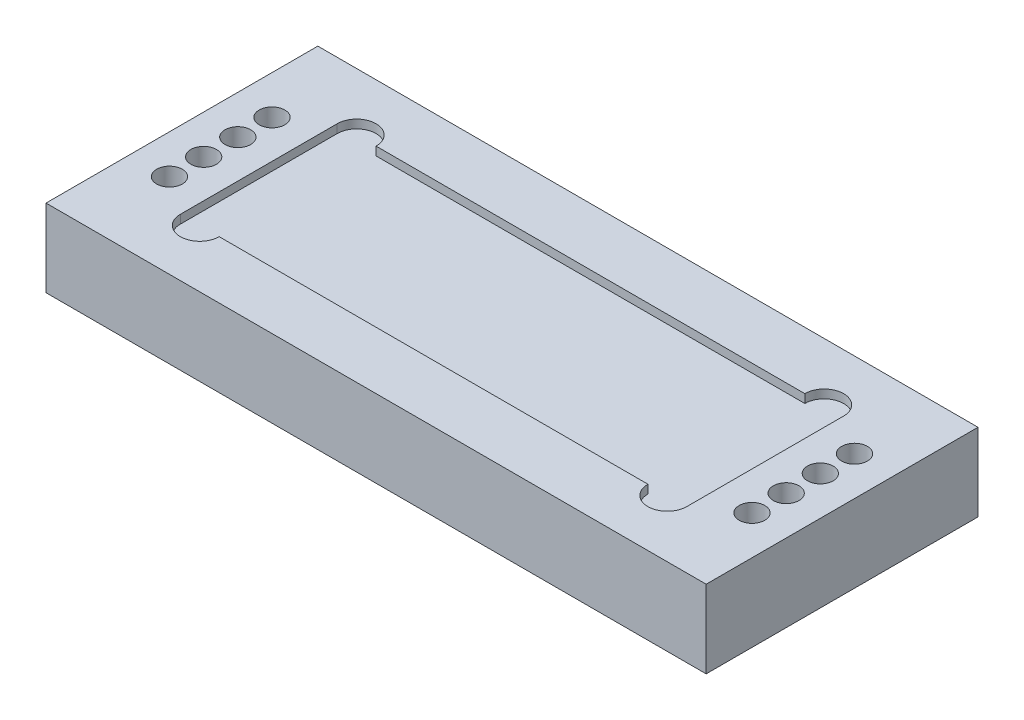
SolidWorks part; units mm, degrees
ref_plane "Front Plane" through (0, 0, 0) normal (0, 0, 1) x (1, 0, 0)
ref_plane "Top Plane" through (0, 0, 0) normal (0, 1, 0) x (1, 0, 0)
ref_plane "Right Plane" through (0, 0, 0) normal (1, 0, 0) x (0, 0, -1)
sketch "Sketch1" plane through (0, 0, 0) normal (0, 1, 0) x (1, 0, 0)
  line L1 (-53.975, 22.225) -> (53.975, 22.225)
  line L2 (-53.975, 22.225) -> (-53.975, -22.225)
  line L3 (-53.975, -22.225) -> (53.975, -22.225)
  line L4 (53.975, 22.225) -> (53.975, -22.225)
  line L5 (-35.052, 12.827) -> (35.052, 12.827) construction
  line L6 (-41.402, 12.827) -> (-41.402, -12.827) construction
  line L7 (-35.052, -12.827) -> (35.052, -12.827) construction
  line L8 (41.402, 12.827) -> (41.402, -12.827) construction
  arc A4 (-35.052, 12.827) -> (-41.402, 12.827) centre (-38.227, 12.827) ccw construction
  arc A5 (-41.402, -12.827) -> (-35.052, -12.827) centre (-38.227, -12.827) ccw construction
  arc A6 (41.402, 12.827) -> (35.052, 12.827) centre (38.227, 12.827) ccw construction
  arc A7 (35.052, -12.827) -> (41.402, -12.827) centre (38.227, -12.827) ccw construction
  point P8 (0, 12.827)
  point P22 (41.402, 0)
  point P24 (0, 22.225)
  point P27 (-53.975, 0)
  dimension "D1" = 3.175
  dimension "D2" = 82.804
  dimension "D3" = 25.654
  dimension "D4" = 107.95
  dimension "D5" = 44.45
extrude "Boss-Extrude1" add sketch "Sketch1" against normal blind 12.7
sketch "Sketch2" plane through (0, 0, 0) normal (0, 1, 0) x (1, 0, 0)
  line L4 (41.402, 12.827) -> (41.402, -12.827) construction
  line L5 (-35.052, -12.827) -> (35.052, -12.827) construction
  line L6 (-41.402, 12.827) -> (-41.402, -12.827) construction
  line L7 (-35.052, 12.827) -> (35.052, 12.827) construction
  line L8 (41.402, 12.827) -> (41.402, -12.827)
  line L9 (-35.052, -12.827) -> (35.052, -12.827)
  line L10 (-41.402, 12.827) -> (-41.402, -12.827)
  line L11 (-35.052, 12.827) -> (35.052, 12.827)
  arc A4 (35.052, -12.827) -> (41.402, -12.827) centre (38.227, -12.827) ccw construction
  arc A5 (-41.402, -12.827) -> (-35.052, -12.827) centre (-38.227, -12.827) ccw construction
  arc A6 (-35.052, 12.827) -> (-41.402, 12.827) centre (-38.227, 12.827) ccw construction
  arc A7 (41.402, 12.827) -> (35.052, 12.827) centre (38.227, 12.827) ccw construction
  arc A8 (35.052, -12.827) -> (41.402, -12.827) centre (38.227, -12.827) ccw
  arc A9 (-41.402, -12.827) -> (-35.052, -12.827) centre (-38.227, -12.827) ccw
  arc A10 (-35.052, 12.827) -> (-41.402, 12.827) centre (-38.227, 12.827) ccw
  arc A11 (41.402, 12.827) -> (35.052, 12.827) centre (38.227, 12.827) ccw
extrude "Cut-Extrude1" cut sketch "Sketch2" against normal blind 1.397
sketch "Sketch3" plane through (0, 0, 0) normal (0, 1, 0) x (1, 0, 0)
  line L0 (-47.625, 8.382) -> (47.625, 8.382) construction
  line L1 (47.625, 8.382) -> (47.625, 2.794) construction
  line L2 (47.625, 2.794) -> (47.625, -2.794) construction
  line L3 (-47.625, -2.794) -> (-47.625, -8.382) construction
  line L4 (-47.625, -2.794) -> (-47.625, 2.794) construction
  line L5 (-47.625, 2.794) -> (-47.625, 8.382) construction
  line L7 (-47.625, -8.382) -> (47.625, -8.382) construction
  line L8 (47.625, -8.382) -> (47.625, -2.794) construction
  point P2 (0, 8.382)
  point P7 (-47.625, 0)
  dimension "D1" = 95.25
  dimension "D2" = 5.588
hole_wizard "M5x0.8 Tapped Hole1" positions "Sketch4" profile "Sketch5" tap size "M5x0.8" standard "ANSI Metric" end condition up to next
sketch "Sketch4" plane through (0, 0, 0) normal (0, 1, 0) x (1, 0, 0)
  point P0 (-47.625, 8.382)
  point P3 (-47.625, 2.794)
  point P6 (-47.625, -2.794)
  point P9 (-47.625, -8.382)
  point P12 (47.625, -8.382)
  point P15 (47.625, -2.794)
  point P18 (47.625, 2.794)
  point P21 (47.625, 8.382)
sketch "Sketch5" plane through (-47.625, 0, -8.382) normal (1, 0, 0) x (0, 0, 1)
  line L0 (0, 0) -> (0, 12.7)
  line L1 (0, 12.7) -> (2.1, 12.7)
  line L2 (2.1, 12.7) -> (2.1, 0)
  line L5 (2.1, 0) -> (0, 0)
  line L11 (0, -6.35) -> (0, 107.95) construction
  dimension "Thru Tap Drill Dia." = 4.2
  dimension "Thru Tap Drill Depth" = 12.7
cosmetic thread "Hole Thread1" parameters "D2"=5
cosmetic thread "Hole Thread2" parameters "D2"=5
cosmetic thread "Hole Thread3" parameters "D2"=5
cosmetic thread "Hole Thread4" parameters "D2"=5
cosmetic thread "Hole Thread5" parameters "D2"=5
cosmetic thread "Hole Thread6" parameters "D2"=5
cosmetic thread "Hole Thread7" parameters "D2"=5
cosmetic thread "Hole Thread8" parameters "D2"=5
